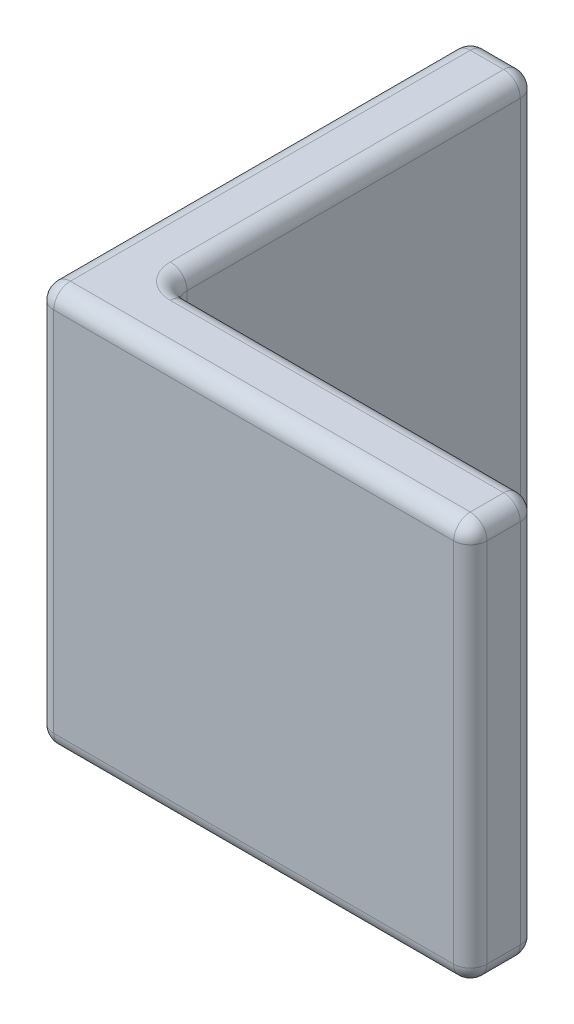
SolidWorks part; units mm, degrees
ref_plane "Front Plane" through (0, 0, 0) normal (0, 0, 1) x (1, 0, 0)
ref_plane "Top Plane" through (0, 0, 0) normal (0, 1, 0) x (1, 0, 0)
ref_plane "Right Plane" through (0, 0, 0) normal (1, 0, 0) x (0, 0, -1)
sketch "Sketch1" plane through (0, 0, 0) normal (0, 1, 0) x (1, 0, 0)
  line L0 (304.8, 1981.2) -> (304.8, 304.8)
  line L1 (0, 0) -> (1981.2, 0)
  line L2 (0, 0) -> (0, 1981.2)
  line L3 (0, 1981.2) -> (304.8, 1981.2)
  line L4 (1981.2, 0) -> (1981.2, 304.8)
  line L5 (304.8, 304.8) -> (1981.2, 304.8)
  dimension "D1" = 1981.2
  dimension "D2" = 304.8
  dimension "D3" = 304.8
extrude "Boss-Extrude1" add sketch "Sketch1" along normal blind 1828.8
fillet "Fillet1" radius 76.2 18 edges at (0, 0, -990.6) (0, 914.4, -1981.2) (152.4, 0, -1981.2) (304.8, 914.4, -1981.2) (304.8, 0, -1143) (304.8, 914.4, -304.8) (1143, 0, -304.8) (1981.2, 914.4, -304.8) (1981.2, 0, -152.4) (0, 914.4, 0) (1981.2, 914.4, 0) (990.6, 0, 0) (152.4, 1828.8, -1981.2) (304.8, 1828.8, -1143) (1143, 1828.8, -304.8) (1981.2, 1828.8, -152.4) (990.6, 1828.8, 0) (0, 1828.8, -990.6)
